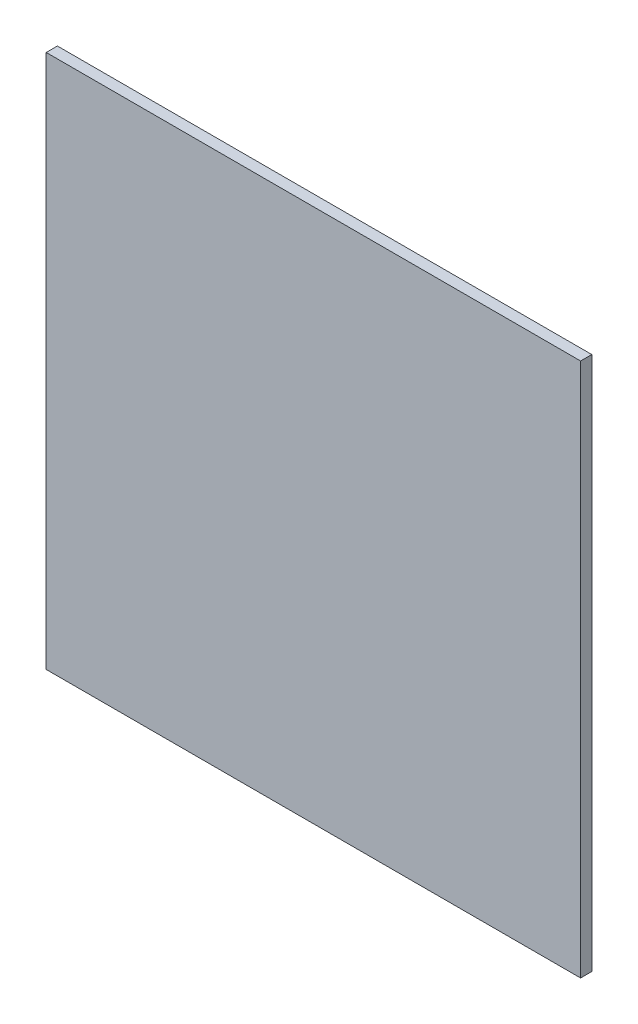
SolidWorks part; units mm, degrees
ref_plane "Front Plane" through (0, 0, 0) normal (0, 0, 1) x (1, 0, 0)
ref_plane "Top Plane" through (0, 0, 0) normal (0, 1, 0) x (1, 0, 0)
ref_plane "Right Plane" through (0, 0, 0) normal (1, 0, 0) x (0, 0, -1)
sketch "Sketch1" plane through (0, 0, 0) normal (0, 0, 1) x (1, 0, 0)
  line L1 (-151.765, 151.765) -> (151.765, 151.765)
  line L2 (-151.765, 151.765) -> (-151.765, -151.765)
  line L3 (-151.765, -151.765) -> (151.765, -151.765)
  line L4 (151.765, 151.765) -> (151.765, -151.765)
  line L5 (-151.765, 151.765) -> (151.765, -151.765) construction
  line L6 (-151.765, -151.765) -> (151.765, 151.765) construction
  point P0 (0, 0)
  dimension "D1" = 303.53
  dimension "D2" = 303.53
extrude "Boss-Extrude1" add sketch "Sketch1" along normal blind 6.35
